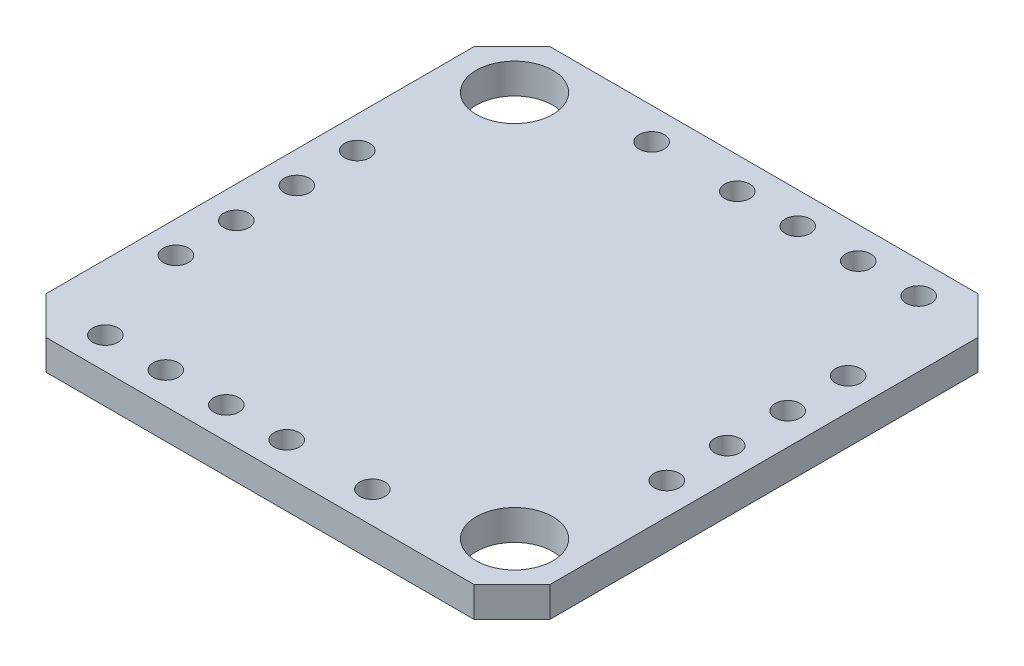
SolidWorks part; units mm, degrees
ref_plane "Front Plane" through (0, 0, 0) normal (0, 0, 1) x (1, 0, 0)
ref_plane "Top Plane" through (0, 0, 0) normal (0, 1, 0) x (1, 0, 0)
ref_plane "Right Plane" through (0, 0, 0) normal (1, 0, 0) x (0, 0, -1)
sketch "Sketch1" plane through (0, 0, 0) normal (0, 1, 0) x (1, 0, 0)
  line L1 (-5, -5) -> (5, -5)
  line L2 (-5, -5) -> (-5, 5)
  line L3 (-5, 5) -> (5, 5)
  line L4 (5, -5) -> (5, 5)
  line L5 (-5, -5) -> (5, 5) construction
  line L6 (-5, 5) -> (5, -5) construction
  point P0 (0, 0)
  dimension "D1" = 10
  dimension "D2" = 10
extrude "Boss-Extrude1" add sketch "Sketch1" along normal blind 0.6
chamfer "Chamfer1" distance 0.75 angle 45 4 edges at (-5, 0.3, -5) (-5, 0.3, 5) (5, 0.3, 5) (5, 0.3, -5)
sketch "Sketch2" plane through (0, 0.6, 0) normal (0, 1, 0) x (1, 0, 0)
  line L0 (-4.625, 4.625) -> (-3.8118, 3.8618) construction
  line L2 (-4.25, 5) -> (-5, 4.25) construction
  circle A0 centre (-3.8118, 3.8618) radius 0.76
extrude "Cut-Extrude1" cut sketch "Sketch2" against normal through all
ref_plane "Plane4" through (0, 0, 0) normal (-0.7071, 0, -0.7071) x (-0.7071, 0, 0.7071)
mirror "Mirror2" about plane through (0, 0, 0) normal (-0.7071, 0, -0.7071) of "Cut-Extrude1"
ref_plane "Plane5" through (0, 0, 0) normal (1, 0, 0) x (0, 0, -1)
ref_plane "Plane6" through (0, 0, 0) normal (0, 0, 1) x (1, 0, 0)
ref_plane "Plane7" through (0, 0, 0) normal (0.7071, 0, -0.7071) x (-0.7071, 0, -0.7071)
sketch "Sketch13" plane through (0, 0.6, 0) normal (0, 1, 0) x (1, 0, 0)
  circle A0 centre (3.8618, -3.8118) radius 0.9598
extrude "Boss-Extrude2" add sketch "Sketch13" against normal up to surface (0.6 mm away) up to face at (3.1018, 0, 3.8118)
sketch "Sketch14" plane through (0, 0.6, 0) normal (0, 1, 0) x (1, 0, 0)
  line L0 (-5, 0) -> (-4.3718, 0) construction
  line L1 (-5, 4.25) -> (-5, -4.25) construction
  line L2 (-4.3718, 0) -> (-4.3718, 0.1) construction
  circle A0 centre (-4.3718, 0.1) radius 0.25
extrude "Cut-Extrude9" cut sketch "Sketch14" against normal up to next
pattern_linear "LPattern5" count 2 spacing 1.2 along (0, 0, -1) count 3 spacing 1.2 along (0, 0, 1) of "Cut-Extrude9"
mirror "Mirror4" about plane through (0, 0, 0) normal (-0.7071, 0, -0.7071) of "Cut-Extrude1"
sketch "Sketch17" plane through (0, 0.6, 0) normal (0, 1, 0) x (1, 0, 0)
  line L0 (0, -5) -> (0, -4.3718) construction
  line L1 (-4.25, -5) -> (4.25, -5) construction
  line L2 (0, -0.33) -> (0, 0.33) construction
  line L3 (0, -4.3718) -> (-2.5, -4.3718) construction
  circle A0 centre (-2.5, -4.3718) radius 0.25
extrude "Cut-Extrude10" cut sketch "Sketch17" against normal up to next
pattern_linear "LPattern6" count 2 spacing 1.2 along (-1, 0, 0) count 3 spacing 1.2 along (1, 0, 0) of "Cut-Extrude10"
sketch "Sketch18" plane through (0, 0.6, 0) normal (0, 1, 0) x (1, 0, 0)
  line L0 (0, 5) -> (0, 4.3718) construction
  line L1 (4.25, 5) -> (-4.25, 5) construction
  line L2 (0, 4.3718) -> (2.5, 4.3718) construction
  circle A0 centre (2.5, 4.3718) radius 0.25
extrude "Cut-Extrude11" cut sketch "Sketch18" against normal up to next
pattern_linear "LPattern7" count 2 spacing 1.2 along (1, 0, 0) count 3 spacing 1.2 along (-1, 0, 0) of "Cut-Extrude11"
sketch "Sketch19" plane through (0, 0.6, 0) normal (0, 1, 0) x (1, 0, 0)
  line L0 (-0.1, -4.3718) -> (1.6, -4.3718) construction
  circle A0 centre (1.6, -4.3718) radius 0.25
extrude "Cut-Extrude12" cut sketch "Sketch19" against normal up to next
sketch "Sketch20" plane through (0, 0.6, 0) normal (0, 1, 0) x (1, 0, 0)
  line L0 (0.1, 4.3718) -> (-1.6, 4.3718) construction
  circle A0 centre (-1.6, 4.3718) radius 0.25
extrude "Cut-Extrude13" cut sketch "Sketch20" against normal up to next
sketch "Sketch21" plane through (0, 0.6, 0) normal (0, 1, 0) x (1, 0, 0)
  line L0 (5, 0) -> (4.3718, 0) construction
  line L1 (5, -4.25) -> (5, 4.25) construction
  line L2 (4.3718, 0) -> (4.3718, -0.1) construction
  circle A0 centre (4.3718, -0.1) radius 0.25
extrude "Cut-Extrude14" cut sketch "Sketch21" against normal up to next
pattern_linear "LPattern8" count 2 spacing 1.2 along (0, 0, 1) count 3 spacing 1.2 along (0, 0, -1) of "Cut-Extrude14"
